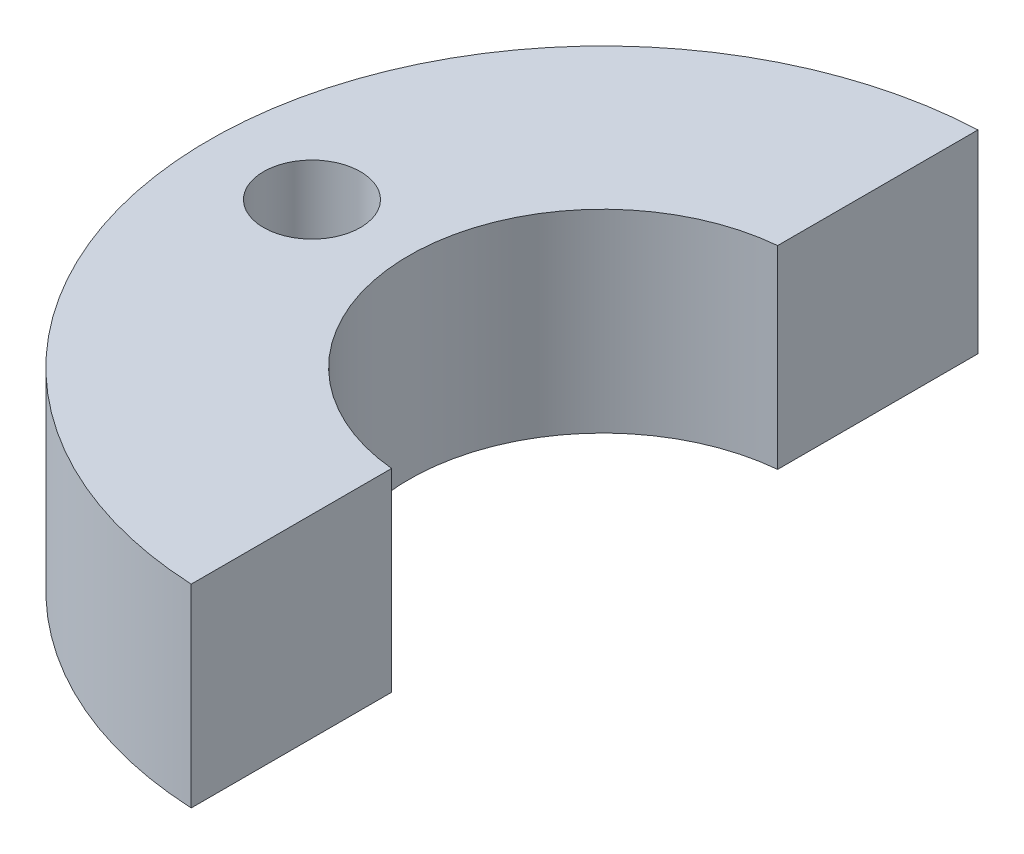
SolidWorks part; units mm, degrees
ref_plane "Front Plane" through (0, 0, 0) normal (0, 0, 1) x (1, 0, 0)
ref_plane "Top Plane" through (0, 0, 0) normal (0, 1, 0) x (1, 0, 0)
ref_plane "Right Plane" through (0, 0, 0) normal (1, 0, 0) x (0, 0, -1)
sketch "Sketch2" plane through (0, 0, 0) normal (0, 1, 0) x (1, 0, 0)
  line L0 (0, 32.5) -> (0, -32.5) construction
  line L1 (-1.5, 32.5) -> (-1.5, 15.9295)
  line L2 (-1.5, -15.9295) -> (-1.5, -32.5)
  line L4 (-1.5, 32.5) -> (-1.5, -32.5) construction
  arc A0 (-1.5, 15.9295) -> (-1.5, -15.9295) centre (0, 0) ccw
  arc A1 (-1.5, 23.9531) -> (-1.5, -23.9531) centre (0, 0) ccw construction
  arc A2 (-1.5, 32.4654) -> (-1.5, -32.4654) centre (0, 0) ccw
  circle A4 centre (-24, 0) radius 4
  circle A6 centre (0, 0) radius 32.5 construction
  circle A7 centre (0, 0) radius 24 construction
  circle A8 centre (0, 0) radius 16 construction
  point P6 (22.9513, 7.0169)
  point P8 (15.3009, 4.6779)
  point P15 (31.0799, 9.5021)
  dimension "D1" = 32
  dimension "D4" = 8
  dimension "D5" = 65
  dimension "D3" = 65
  dimension "D6" = 24
  dimension "D2" = 1.5
extrude "Boss-Extrude2" add sketch "Sketch2" along normal mid plane 16 contours L1 A2 L2 A0 A4
sketch "Sketch6" plane through (-1.5, 0, 0) normal (1, 0, 0) x (0, 0, -1)
  line L0 (-24.1974, 8) -> (-24.1974, -8) construction
  line L1 (-15.9295, 8) -> (-32.4654, 8) construction
  line L2 (-15.9295, -8) -> (-32.4654, -8) construction
